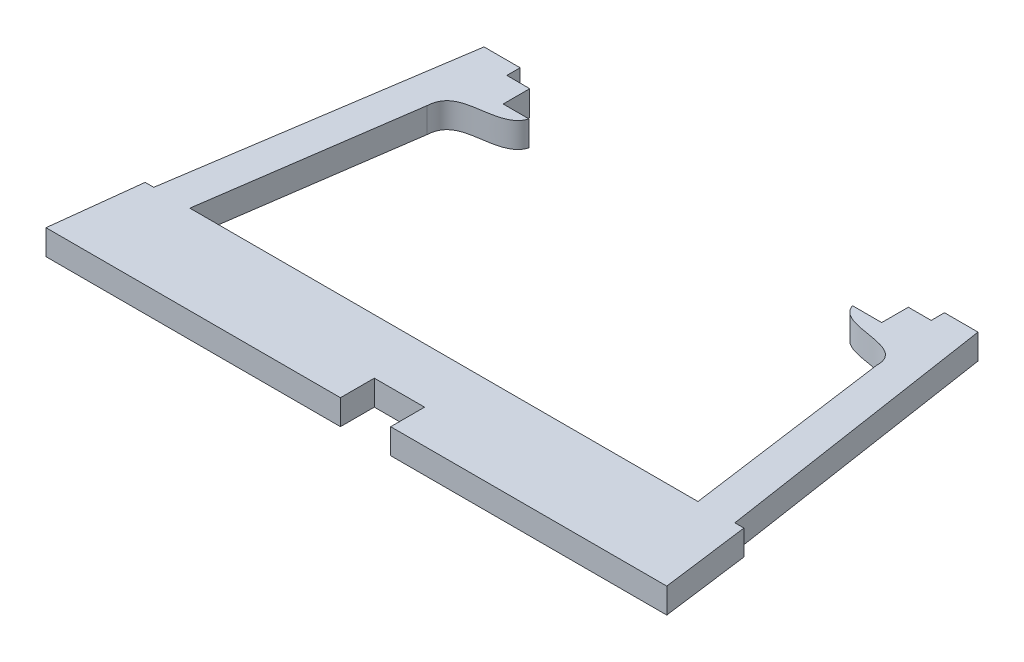
SolidWorks part; units mm, degrees
ref_plane "前视基准面" through (0, 0, 0) normal (0, 0, 1) x (1, 0, 0)
ref_plane "上视基准面" through (0, 0, 0) normal (0, 1, 0) x (1, 0, 0)
ref_plane "右视基准面" through (0, 0, 0) normal (1, 0, 0) x (0, 0, -1)
sketch "草图1" plane through (0, 0, 0) normal (0, 1, 0) x (1, 0, 0)
  line L0 (-49.404, -126.0149) -> (-51.2674, -111.8705)
  line L1 (-51.2674, -111.8705) -> (-52.7072, -111.8705)
  line L2 (-52.7072, -111.8705) -> (-59.6524, -66.2188)
  line L3 (-59.6524, -66.2188) -> (-64.9883, -66.2188)
  line L4 (-64.9883, -66.2188) -> (-64.9883, -68.3363)
  line L5 (-64.9883, -68.3363) -> (-68.6302, -68.3363)
  line L6 (-68.6302, -68.3363) -> (-68.6302, -72.5711)
  line L7 (-68.6302, -72.5711) -> (-73.2886, -72.5711)
  line L9 (-49.404, -126.0149) -> (-93.356, -126.0149)
  line L10 (-93.356, -126.0149) -> (-93.356, -120.6249)
  line L11 (-93.356, -120.6249) -> (-101.356, -120.6249)
  line L12 (-101.356, -120.6249) -> (-101.356, -126.0149)
  line L13 (-101.356, -126.0149) -> (-148.2327, -126.0149)
  line L14 (-148.2327, -126.0149) -> (-146.5911, -111.8705)
  line L15 (-146.5911, -111.8705) -> (-145.2231, -111.8705)
  line L16 (-145.2231, -111.8705) -> (-138.2919, -66.2188)
  line L17 (-138.2919, -66.2188) -> (-132.5463, -66.2188)
  line L18 (-132.5463, -66.2188) -> (-132.5463, -68.3363)
  line L19 (-132.5463, -68.3363) -> (-128.8983, -68.3363)
  line L20 (-128.8983, -68.3363) -> (-128.8983, -72.5711)
  line L21 (-128.8983, -72.5711) -> (-124.7943, -72.5711)
  line L22 (-134.7351, -78.8628) -> (-139.4775, -111.8705)
  line L23 (-139.4775, -111.8705) -> (-58.5834, -111.8705)
  line L24 (-58.5834, -111.8705) -> (-63.1434, -78.8628)
  spline S0 degree 3 poles (-124.7943, -72.5711) (-125.278, -74.2328) (-129.8768, -75.4778) (-134.5293, -75.5672) (-134.7351, -78.8628) knots 0 0 0 0 0.392721 1 1 1 1
  spline S1 degree 3 poles (-63.1434, -78.8628) (-62.9924, -73.6629) (-71.9075, -76.7032) (-73.2886, -72.5711) knots 0 0 0 0 1 1 1 1
  dimension "D1" = 8
  dimension "D2" = 5.39
extrude "凸台-拉伸1" add sketch "草图1" along normal blind 4
